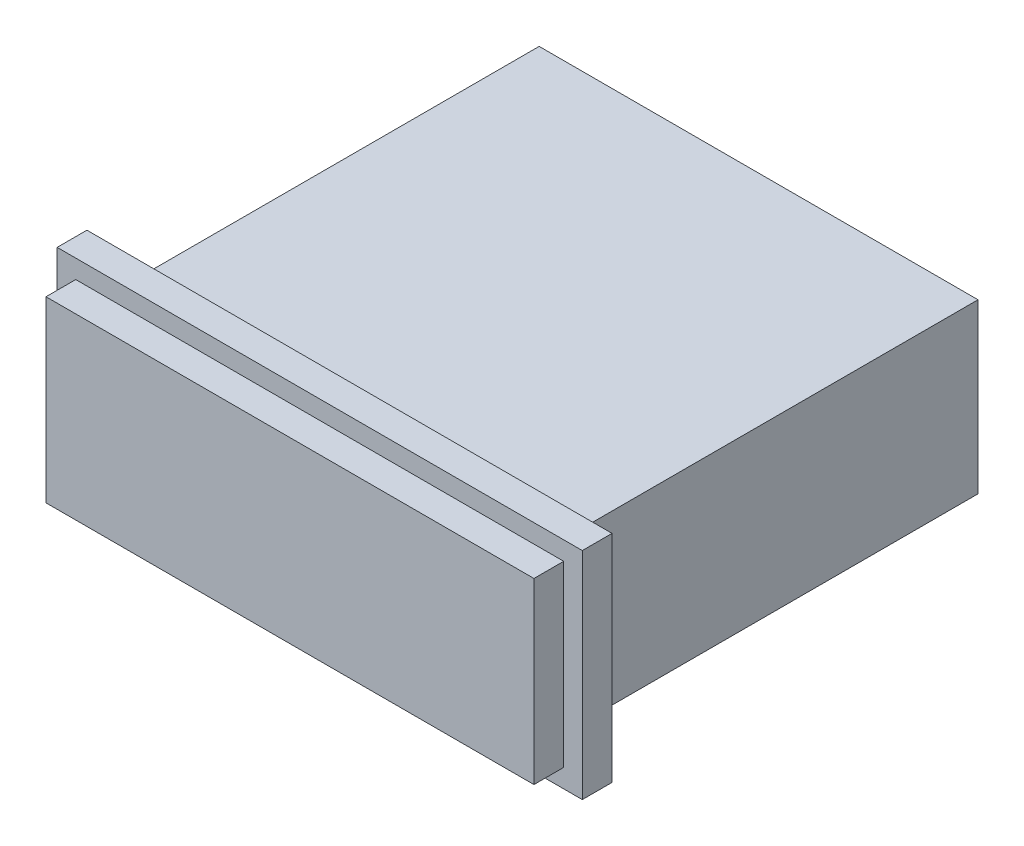
SolidWorks part; units mm, degrees
ref_plane "Спереди" through (0, 0, 0) normal (0, 0, 1) x (1, 0, 0)
ref_plane "Сверху" through (0, 0, 0) normal (0, 1, 0) x (1, 0, 0)
ref_plane "Справа" through (0, 0, 0) normal (1, 0, 0) x (0, 0, -1)
sketch "Эскиз1" plane through (0, 0, 0) normal (0, 0, 1) x (1, 0, 0)
  line L1 (-17.65, -7.25) -> (17.65, -7.25)
  line L2 (-17.65, -7.25) -> (-17.65, 7.25)
  line L3 (-17.65, 7.25) -> (17.65, 7.25)
  line L4 (17.65, -7.25) -> (17.65, 7.25)
  line L5 (-17.65, -7.25) -> (17.65, 7.25) construction
  line L6 (-17.65, 7.25) -> (17.65, -7.25) construction
  point P0 (0, 0)
  dimension "D1" = 35.3
  dimension "D2" = 14.5
extrude "Бобышка-Вытянуть1" add sketch "Эскиз1" against normal blind 4
sketch "Эскиз2" plane through (0, 0, 0) normal (0, 0, 1) x (1, 0, 0)
  line L1 (-17.65, 7.25) -> (17.65, 7.25)
  line L2 (-17.65, 7.25) -> (-17.65, -7.25)
  line L3 (-17.65, -7.25) -> (17.65, -7.25)
  line L4 (17.65, 7.25) -> (17.65, -7.25)
extrude "Вырез-Вытянуть-Тонкостенный1" cut sketch "Эскиз2" against normal blind 2 thin
sketch "Эскиз3" plane through (0, 0, -4) normal (0, 0, -1) x (-1, 0, 0)
  line L1 (-14.75, -5.65) -> (14.75, -5.65)
  line L2 (-14.75, -5.65) -> (-14.75, 5.65)
  line L3 (-14.75, 5.65) -> (14.75, 5.65)
  line L4 (14.75, -5.65) -> (14.75, 5.65)
  line L5 (-14.75, -5.65) -> (14.75, 5.65) construction
  line L6 (-14.75, 5.65) -> (14.75, -5.65) construction
  point P0 (0, 0)
  dimension "D1" = 29.5
  dimension "D2" = 11.3
extrude "Бобышка-Вытянуть2" add sketch "Эскиз3" along normal blind 27.5
